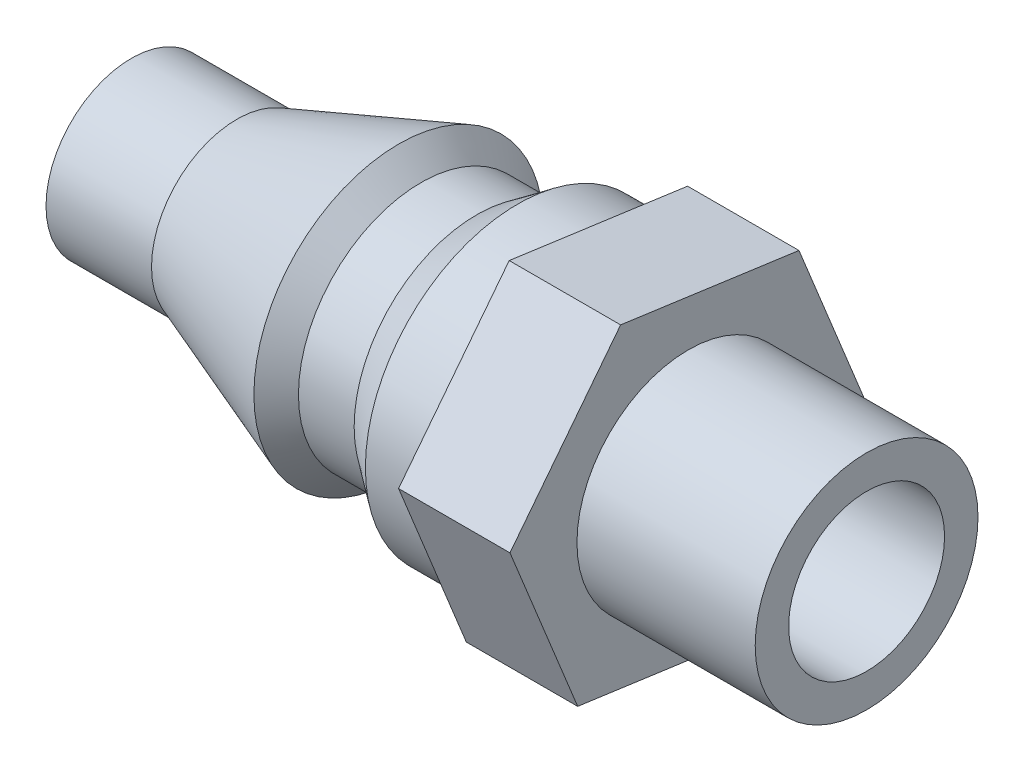
SolidWorks part; units mm, degrees
ref_plane "前视基准面" through (0, 0, 0) normal (0, 0, 1) x (1, 0, 0)
ref_plane "上视基准面" through (0, 0, 0) normal (0, 1, 0) x (1, 0, 0)
ref_plane "右视基准面" through (0, 0, 0) normal (1, 0, 0) x (0, 0, -1)
sketch "草图1" plane through (0, 0, 0) normal (0, 1, 0) x (1, 0, 0)
  line L0 (0, 0) -> (29.549, 0) construction
  line L1 (0, 3.048) -> (0, 3.8305)
  line L2 (0, 3.8305) -> (4.7359, 3.8305)
  line L3 (4.7359, 3.8305) -> (12, 6.5)
  line L4 (12, 6.5) -> (13, 5.5)
  line L5 (13, 5.5) -> (15.5, 5.5)
  line L6 (15.5, 5.5) -> (17.339, 6.8348)
  line L7 (17.339, 6.8348) -> (20, 6.8348)
  line L8 (20, 6.8348) -> (20, 3.4174)
  line L9 (0, 3.048) -> (20, 3.4174)
  dimension "D1" = 6.5
  dimension "D2" = 5.5
  dimension "D3" = 12
  dimension "D4" = 13
  dimension "D5" = 2.5
  dimension "D6" = 20
revolve "旋转1" add sketch "草图1" angle 360 about L0
sketch "草图2" plane through (20, 0, 0) normal (1, 0, 0) x (0, 0, -1)
  line L1 (8.0061, -1.1113) -> (4.9655, 6.3779)
  line L2 (4.9655, 6.3779) -> (-3.0407, 7.4892)
  line L3 (-3.0407, 7.4892) -> (-8.0061, 1.1113)
  line L4 (-8.0061, 1.1113) -> (-4.9655, -6.3779)
  line L5 (-4.9655, -6.3779) -> (3.0407, -7.4892)
  line L6 (3.0407, -7.4892) -> (8.0061, -1.1113)
  circle A0 centre (0, 0) radius 7 construction
  dimension "D1" = 14
extrude "拉伸1" add sketch "草图2" along normal blind 5
sketch "草图3" plane through (25, 0, 0) normal (1, 0, 0) x (0, 0, -1)
  circle A0 centre (0, 0) radius 5
  dimension "D1" = 10
extrude "拉伸2" add sketch "草图3" along normal blind 8
sketch "草图4" plane through (33, 0, 0) normal (1, 0, 0) x (0, 0, -1)
  circle A0 centre (0, 0) radius 3.5
  dimension "D1" = 7
extrude "拉伸3" cut sketch "草图4" against normal through all
